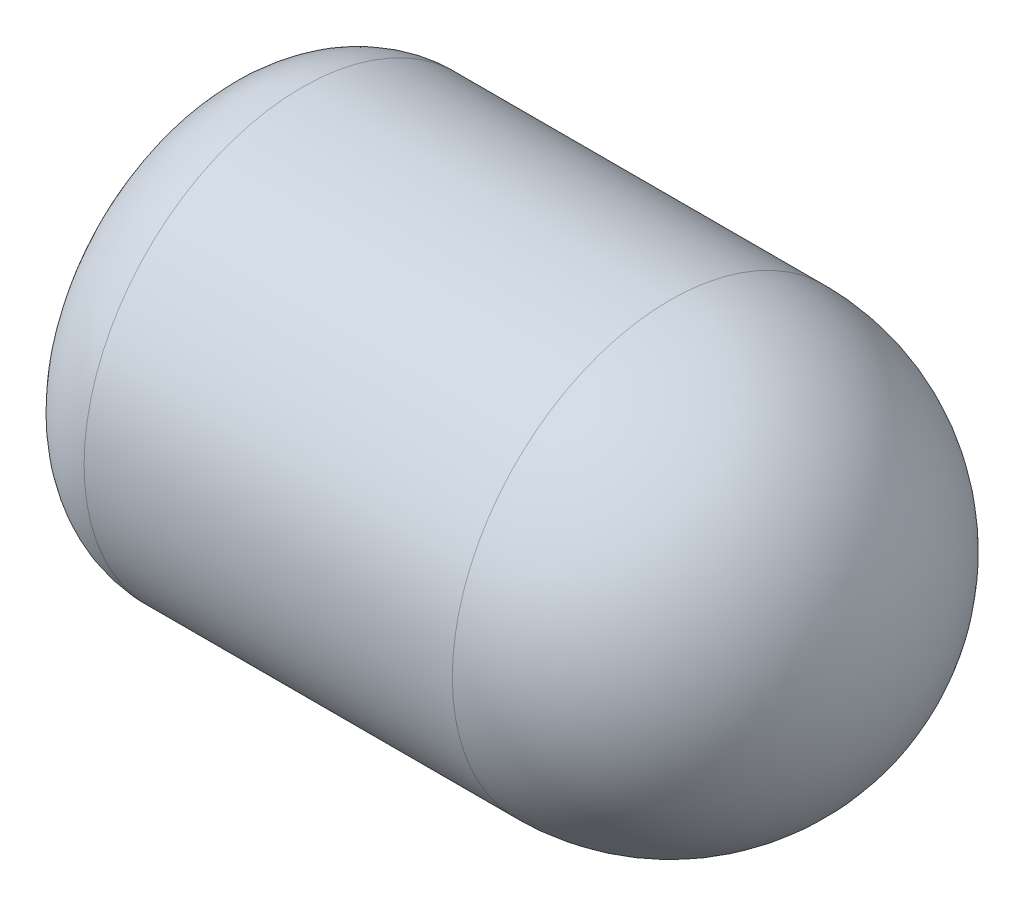
SolidWorks part; units mm, degrees
ref_plane "Plan de face" through (0, 0, 0) normal (0, 0, 1) x (1, 0, 0)
ref_plane "Plan de dessus" through (0, 0, 0) normal (0, 1, 0) x (1, 0, 0)
ref_plane "Plan de droite" through (0, 0, 0) normal (1, 0, 0) x (0, 0, -1)
sketch "Esquisse2" plane through (0, 0, 0) normal (0, 0, 1) x (1, 0, 0)
  line L0 (-13.0301, 0) -> (18.8919, 0) construction
  line L1 (0, 3.1) -> (0, 0)
  line L2 (0, 7.1) -> (-15, 7.1)
  line L4 (0, 3.1) -> (-15, 3.1)
  line L5 (-15, 7.1) -> (-15, 3.1)
  line L6 (0, 0) -> (7.1, 0)
  arc A0 (7.1, 0) -> (0, 7.1) centre (0, 0) ccw
  dimension "D4" = 7.1
  dimension "D1" = 15
  dimension "D2" = 4
  dimension "D3" = 3.1
revolve "Révolution1" add sketch "Esquisse2" angle 360 about L0
fillet "Congé1" radius 3 1 edges at (-15, 0, 7.1)
